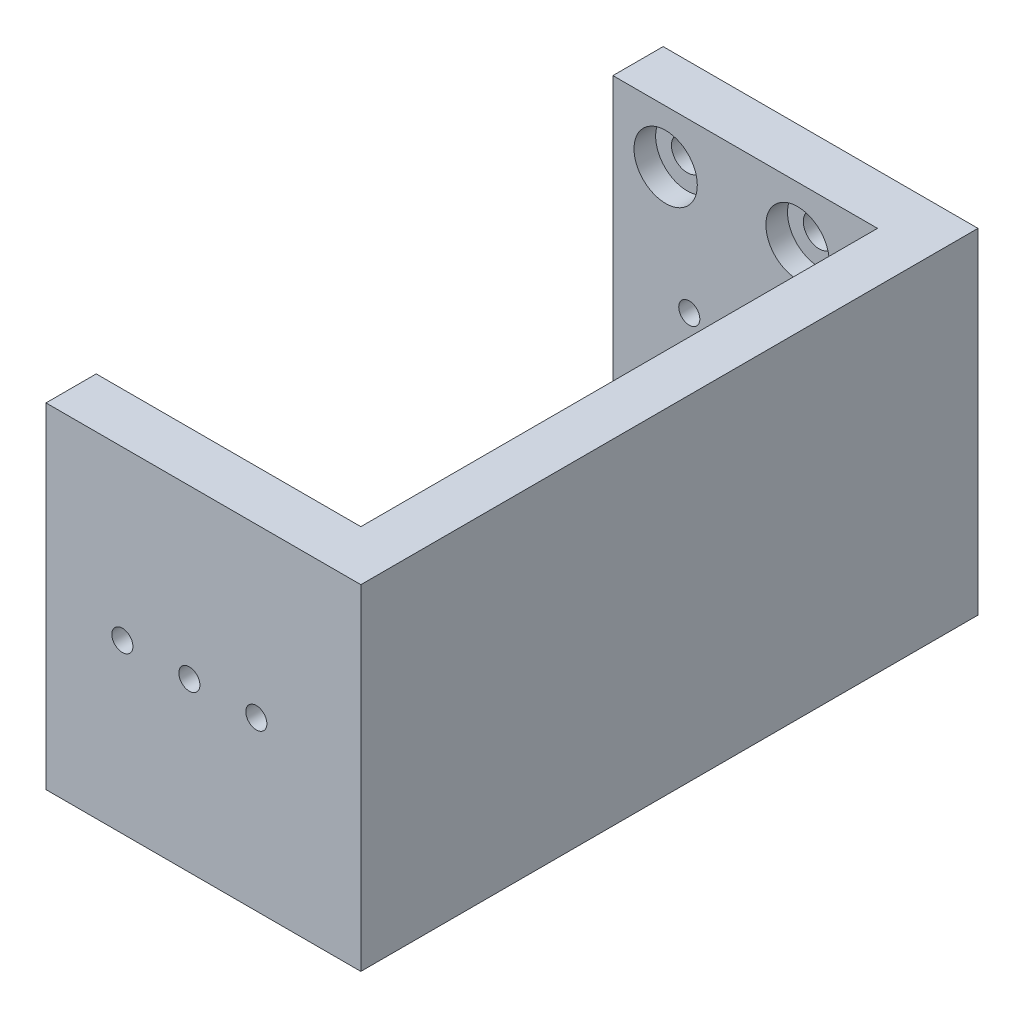
SolidWorks part; units mm, degrees
ref_plane "Front Plane" through (0, 0, 0) normal (0, 0, 1) x (1, 0, 0)
ref_plane "Top Plane" through (0, 0, 0) normal (0, 1, 0) x (1, 0, 0)
ref_plane "Right Plane" through (0, 0, 0) normal (1, 0, 0) x (0, 0, -1)
sketch "Sketch1" plane through (0, 0, 0) normal (0, 0, 1) x (1, 0, 0)
  line L0 (-27.178, -31.75) -> (32.512, -31.75)
  line L1 (32.512, -31.75) -> (32.512, 31.75)
  line L2 (32.512, 31.75) -> (-27.178, 31.75)
  line L3 (-27.178, 31.75) -> (-27.178, -31.75)
  circle A0 centre (-12.7, 0) radius 2
  circle A1 centre (0, 0) radius 2
  circle A2 centre (12.7, 0) radius 2
extrude "Boss-Extrude1" add sketch "Sketch1" along normal blind 117
sketch "Sketch2" plane through (0, -31.75, 0) normal (0, -1, 0) x (1, 0, 0)
  line L0 (-27.178, 117) -> (-27.178, 0) construction
  line L1 (-27.178, 107.475) -> (22.987, 107.475)
  line L2 (-27.178, 107.475) -> (-27.178, 9.525)
  line L3 (-27.178, 9.525) -> (22.987, 9.525)
  line L4 (22.987, 107.475) -> (22.987, 9.525)
  line L5 (-27.178, 117) -> (32.512, 117) construction
  line L6 (32.512, 117) -> (32.512, 0) construction
  line L7 (-27.178, 0) -> (32.512, 0) construction
  dimension "D1" = 9.525
  dimension "D2" = 9.525
  dimension "D3" = 9.525
extrude "Cut-Extrude1" cut sketch "Sketch2" against normal through all
sketch "Sketch3" plane through (0, 0, 9.525) normal (0, 0, 1) x (1, 0, 0)
  line L0 (-27.178, 31.75) -> (-27.178, -31.75) construction
  line L1 (-27.178, -31.75) -> (22.987, -31.75) construction
  line L2 (-27.178, 31.75) -> (22.987, 31.75) construction
  circle A0 centre (-17.178, -21.75) radius 6
  circle A1 centre (7.822, -21.75) radius 6
  circle A2 centre (-17.178, -21.75) radius 3
  circle A3 centre (7.822, -21.75) radius 3
  circle A4 centre (-17.178, 21.75) radius 6
  circle A5 centre (7.822, 21.75) radius 6
  circle A6 centre (-17.178, 21.75) radius 3
  circle A7 centre (7.822, 21.75) radius 3
  dimension "D2" = 12
  dimension "D3" = 6
  dimension "D4" = 12
  dimension "D5" = 6
  dimension "D6" = 25
  dimension "D7" = 10
  dimension "D8" = 12
  dimension "D9" = 6
  dimension "D10" = 12
  dimension "D11" = 6
  dimension "D12" = 10
  dimension "D13" = 10
extrude "Cut-Extrude2" cut sketch "Sketch3" against normal blind 4.1
sketch "Sketch5" plane through (0, 0, 9.525) normal (0, 0, 1) x (1, 0, 0)
  circle A0 centre (-17.178, 21.75) radius 3 construction
  circle A1 centre (7.822, 21.75) radius 3 construction
  circle A2 centre (7.822, -21.75) radius 3 construction
  circle A3 centre (-17.178, -21.75) radius 3 construction
  circle A4 centre (-17.178, 21.75) radius 3
  circle A5 centre (7.822, 21.75) radius 3
  circle A6 centre (7.822, -21.75) radius 3
  circle A7 centre (-17.178, -21.75) radius 3
extrude "Cut-Extrude3" cut sketch "Sketch5" against normal through all
